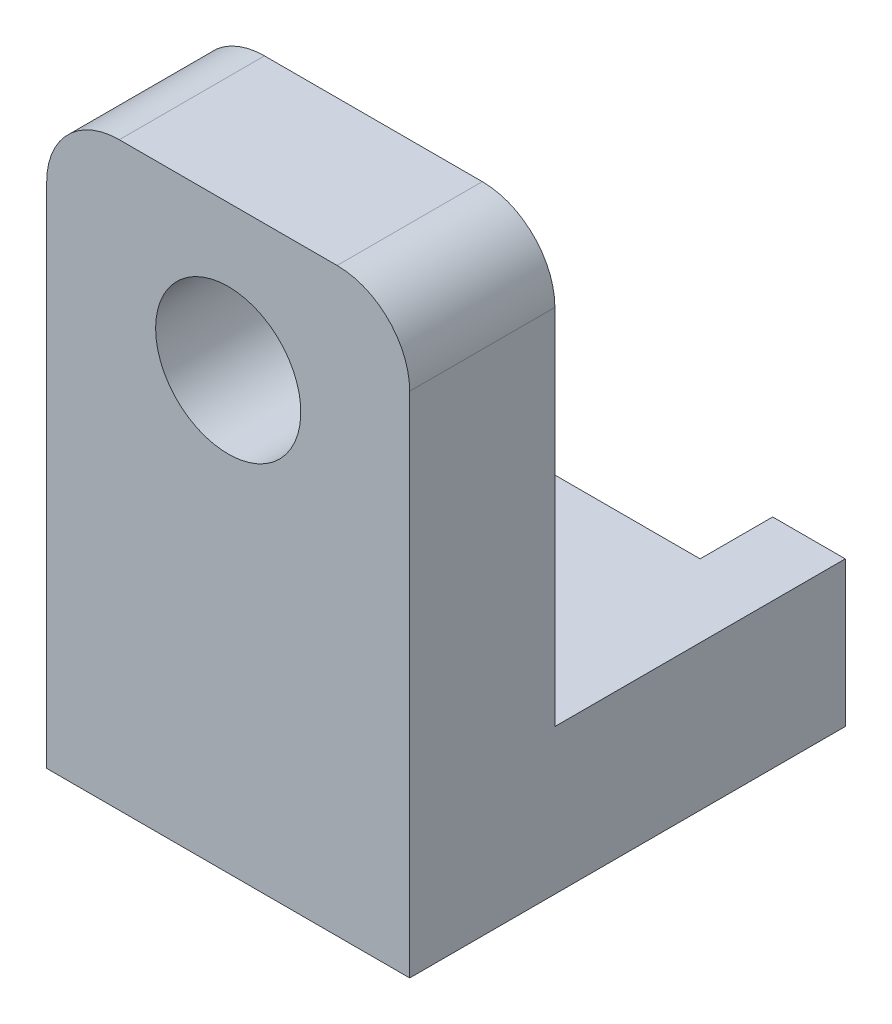
SolidWorks part; units mm, degrees
ref_plane "Piano frontale" through (0, 0, 0) normal (0, 0, 1) x (1, 0, 0)
ref_plane "Piano superiore" through (0, 0, 0) normal (0, 1, 0) x (1, 0, 0)
ref_plane "Piano destro" through (0, 0, 0) normal (1, 0, 0) x (0, 0, -1)
sketch "Schizzo1" plane through (0, 0, 0) normal (1, 0, 0) x (0, 0, -1)
  line L6 (0, 0) -> (0, 40)
  line L7 (0, 40) -> (10, 40)
  line L8 (10, 40) -> (10, 10)
  line L9 (10, 10) -> (30, 10)
  line L10 (30, 10) -> (30, 0)
  line L11 (30, 0) -> (0, 0)
  dimension "D1" = 10
  dimension "D2" = 10
  dimension "D3" = 40
  dimension "D4" = 30
extrude "Estrusione-Estrusione1" add sketch "Schizzo1" along normal mid plane 25
sketch "Schizzo2" plane through (0, 10, 0) normal (0, 1, 0) x (1, 0, 0)
  line L0 (0, 0) -> (0, 25) construction
  line L1 (12.5, 30) -> (-12.5, 30) construction
  line L2 (-7.5, 25) -> (7.5, 25)
  line L3 (7.5, 25) -> (7.5, 30)
  line L4 (-7.5, 25) -> (-7.5, 30)
  point P8 (0, 25)
  line M7 (12.5, 30) -> (-12.5, 30)
  dimension "D1" = 15
  dimension "D2" = 5
extrude "Taglio-Estrusione1" cut sketch "Schizzo2" against normal through all and the other way through all contours L4 L2 L3 M7
hole_wizard "Foro Ø10.0 (10)-1" positions "Schizzo3" profile "Schizzo4" hole size "Ø10.0" standard "ISO" end condition up to next
sketch "Schizzo3" plane through (0, 0, -10) normal (0, 0, -1) x (-1, 0, 0)
  line L0 (0, 40) -> (0, 20) construction
  line L1 (-12.5, 40) -> (12.5, 40) construction
  line L5 (-12.5, 0) -> (-7.5, 0) construction
  point P17 (0, 30)
  dimension "D1" = 30
sketch "Schizzo4" plane through (0, 30, -10) normal (1, 0, 0) x (0, 1, 0)
  line L0 (0, 0) -> (0, 10)
  line L1 (0, 10) -> (5, 10)
  line L2 (5, 10) -> (5, 0)
  line L5 (5, 0) -> (0, 0)
  line L11 (0, -6.35) -> (0, 107.95) construction
  dimension "Thru Hole Dia." = 10
  dimension "Thru Hole Depth" = 10
fillet "Raccordo1" radius 5 2 edges at (-12.5, 40, -5) (12.5, 40, -5)
